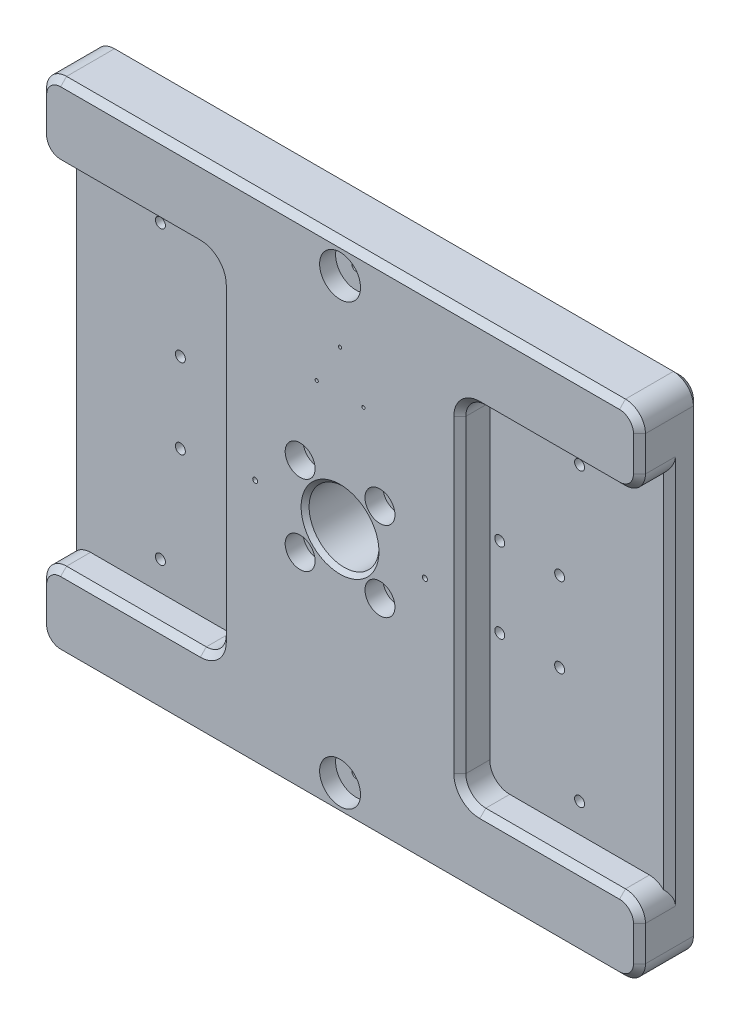
SolidWorks part; units mm, degrees
ref_plane "前视基准面" through (0, 0, 0) normal (0, 0, 1) x (1, 0, 0)
ref_plane "上视基准面" through (0, 0, 0) normal (0, 1, 0) x (1, 0, 0)
ref_plane "右视基准面" through (0, 0, 0) normal (1, 0, 0) x (0, 0, -1)
sketch "草图1" plane through (0, 0, 0) normal (0, 0, 1) x (1, 0, 0)
  line L1 (-150, 125) -> (150, 125)
  line L2 (-150, 125) -> (-150, -125)
  line L3 (-150, -125) -> (150, -125)
  line L4 (150, 125) -> (150, -125)
  line L5 (-150, 125) -> (150, -125) construction
  line L6 (-150, -125) -> (150, 125) construction
  point P0 (0, 0)
  dimension "D1" = 300
  dimension "D2" = 250
extrude "凸台-拉伸1" add sketch "草图1" along normal blind 30
sketch "草图2" plane through (0, 0, 30) normal (0, 0, 1) x (1, 0, 0)
  line L0 (-150, 125) -> (-150, -125) construction
  line L1 (-240, 87.5) -> (-60, 87.5)
  line L2 (-240, 87.5) -> (-240, -87.5)
  line L3 (-240, -87.5) -> (-60, -87.5)
  line L4 (-60, 87.5) -> (-60, -87.5)
  line L5 (-240, 87.5) -> (-60, -87.5) construction
  line L6 (-240, -87.5) -> (-60, 87.5) construction
  line L7 (150, -125) -> (150, 125) construction
  line L8 (240, -87.5) -> (60, -87.5)
  line L9 (240, -87.5) -> (240, 87.5)
  line L10 (240, 87.5) -> (60, 87.5)
  line L11 (60, -87.5) -> (60, 87.5)
  line L12 (240, -87.5) -> (60, 87.5) construction
  line L13 (240, 87.5) -> (60, -87.5) construction
  point P0 (-150, 0)
  point P7 (150, 0)
  dimension "D1" = 175
  dimension "D2" = 90
extrude "切除-拉伸1" cut sketch "草图2" against normal blind 15
fillet "圆角1" radius 10 12 edges at (150, -87.5, 22.5) (60, -87.5, 22.5) (150, 87.5, 22.5) (60, 87.5, 22.5) (-150, -87.5, 22.5) (-60, -87.5, 22.5) (-150, 87.5, 22.5) (-60, 87.5, 22.5) (-150, -125, 15) (150, -125, 15) (150, 125, 15) (-150, 125, 15)
hole_wizard "打孔尺寸(%根据)内六角圆柱头螺钉的类型1" positions "草图4" profile "草图5" counterbore size "M8" standard "GB" end condition through all
sketch "草图4" plane through (0, 0, 30) normal (0, 0, 1) x (1, 0, 0)
  point P0 (-20, 20)
  point P3 (20, 20)
  point P6 (20, -20)
  point P9 (-20, -20)
sketch "草图5" plane through (-20, 20, 30) normal (1, 0, 0) x (0, -1, 0)
  line L0 (0, 0) -> (0, 30)
  line L1 (0, 30) -> (4.5, 30)
  line L3 (4.5, 30) -> (4.5, 9)
  line L4 (4.5, 9) -> (7.5, 9)
  line L5 (7.5, 9) -> (7.5, 0)
  line L7 (7.5, 0) -> (0, 0)
  line L11 (0, -6.35) -> (0, 107.95) construction
  dimension "通孔孔直径" = 9
  dimension "通孔孔深度" = 30
  dimension "柱形沉头孔直径" = 15
  dimension "柱形沉头孔深度" = 9
chamfer "倒角1" distance 3 angle 45 34 edges at (0, -125, 0) (147.0711, -122.0711, 0) (-147.0711, -122.0711, 0) (150, 0, 0) (-150, 0, 0) (147.0711, 122.0711, 0) (-147.0711, 122.0711, 0) (0, 125, 0) (-105, 87.5, 30) (-147.0711, 90.4289, 30) (-62.9289, 84.5711, 30) (-150, 106.25, 30) (-60, 0, 30) (-147.0711, 122.0711, 30) (-62.9289, -84.5711, 30) (0, 125, 30) (-105, -87.5, 30) (147.0711, 122.0711, 30) (-147.0711, -90.4289, 30) (150, 106.25, 30) (-150, -106.25, 30) (147.0711, 90.4289, 30) (-147.0711, -122.0711, 30) (105, 87.5, 30) (0, -125, 30) (62.9289, 84.5711, 30) (147.0711, -122.0711, 30) (60, 0, 30) (150, -106.25, 30) (62.9289, -84.5711, 30) (147.0711, -90.4289, 30) (105, -87.5, 30) (-150, 0, 15) (150, 0, 15)
sketch "草图6" plane through (0, 0, 30) normal (0, 0, 1) x (1, 0, 0)
  circle A0 centre (0, 0) radius 17.5
  dimension "D1" = 35
extrude "切除-拉伸2" cut sketch "草图6" against normal through all
chamfer "倒角2" distance 2 angle 45 2 edges at (17.5, 0, 0) (17.5, 0, 30)
hole_wizard "M6 螺纹孔1" positions "草图7" profile "草图9" tap size "M6" standard "GB"
sketch "草图7" plane through (0, 0, 0) normal (0, 0, -1) x (-1, 0, 0)
  line L0 (23.3, -95) -> (16.7, -95) construction
  line L1 (23.3, -101) -> (23.3, -89) construction
  line L2 (16.7, -89) -> (16.7, -101) construction
  line L3 (-16.7, -95) -> (-23.3, -95) construction
  line L4 (-16.7, -101) -> (-16.7, -89) construction
  line L5 (-23.3, -89) -> (-23.3, -101) construction
  line L8 (-23.3, -65) -> (-16.7, -65) construction
  line L9 (-23.3, -59) -> (-23.3, -71) construction
  line L11 (-16.7, -71) -> (-16.7, -59) construction
  line L12 (23.3, -65) -> (16.7, -65) construction
  line L13 (23.3, -71) -> (23.3, -59) construction
  line L14 (16.7, -59) -> (16.7, -71) construction
  line L15 (65, -23.3) -> (65, -16.7) construction
  line L16 (59, -23.3) -> (71, -23.3) construction
  line L17 (71, -16.7) -> (59, -16.7) construction
  line L20 (95, -23.3) -> (95, -16.7) construction
  line L21 (89, -23.3) -> (101, -23.3) construction
  line L22 (101, -16.7) -> (89, -16.7) construction
  line L25 (95, 16.7) -> (95, 23.3) construction
  line L26 (89, 16.7) -> (101, 16.7) construction
  line L27 (101, 23.3) -> (89, 23.3) construction
  line L30 (65, 16.7) -> (65, 23.3) construction
  line L31 (59, 16.7) -> (71, 16.7) construction
  line L33 (71, 23.3) -> (59, 23.3) construction
  line L34 (-65, -23.3) -> (-65, -16.7) construction
  line L35 (-71, -23.3) -> (-59, -23.3) construction
  line L36 (-59, -16.7) -> (-71, -16.7) construction
  line L39 (-95, -23.3) -> (-95, -16.7) construction
  line L40 (-101, -23.3) -> (-89, -23.3) construction
  line L41 (-89, -16.7) -> (-101, -16.7) construction
  line L45 (-65, 16.7) -> (-65, 23.3) construction
  line L46 (-71, 16.7) -> (-59, 16.7) construction
  line L47 (-59, 23.3) -> (-71, 23.3) construction
  line L51 (-95, 16.7) -> (-95, 23.3) construction
  line L52 (-101, 16.7) -> (-89, 16.7) construction
  line L53 (-89, 23.3) -> (-101, 23.3) construction
  line L55 (23.3, 65) -> (16.7, 65) construction
  line L56 (23.3, 59) -> (23.3, 71) construction
  line L57 (16.7, 71) -> (16.7, 59) construction
  line L60 (-16.7, 65) -> (-23.3, 65) construction
  line L61 (-16.7, 59) -> (-16.7, 71) construction
  line L62 (-23.3, 71) -> (-23.3, 59) construction
  line L65 (23.3, 95) -> (16.7, 95) construction
  line L66 (23.3, 89) -> (23.3, 101) construction
  line L67 (16.7, 101) -> (16.7, 89) construction
  line L71 (-16.7, 95) -> (-23.3, 95) construction
  line L72 (-16.7, 89) -> (-16.7, 101) construction
  line L73 (-23.3, 101) -> (-23.3, 89) construction
  point P11 (20, -95)
  point P39 (-20, -95)
  point P41 (-20, -65)
  point P43 (20, -65)
  point P81 (65, -20)
  point P83 (95, -20)
  point P85 (95, 20)
  point P87 (65, 20)
  point P169 (-65, -20)
  point P171 (-95, -20)
  point P173 (-95, 20)
  point P175 (-65, 20)
  point P177 (20, 65)
  point P179 (20, 95)
  point P181 (-20, 65)
  point P183 (-20, 95)
sketch "草图9" plane through (20, 95, 0) normal (1, 0, 0) x (0, 1, 0)
  line L0 (0, 0) -> (0, 16.5022)
  line L1 (0, 16.5022) -> (2.5, 15)
  line L2 (2.5, 15) -> (2.5, 0)
  line L5 (2.5, 0) -> (0, 0)
  line L10 (0, 16.5022) -> (-2.5, 15) construction
  line L11 (0, -6.35) -> (0, 107.95) construction
  dimension "螺纹孔钻头直径" = 5
  dimension "螺纹孔钻头深度" = 15
  dimension "导头角度" = 118
cosmetic thread "孔螺蚊线1" parameters "D1"=12, "D2"=6
cosmetic thread "孔螺蚊线2" parameters "D1"=12, "D2"=6
cosmetic thread "孔螺蚊线3" parameters "D1"=12, "D2"=6
cosmetic thread "孔螺蚊线4" parameters "D1"=12, "D2"=6
cosmetic thread "孔螺蚊线5" parameters "D1"=12, "D2"=6
cosmetic thread "孔螺蚊线6" parameters "D1"=12, "D2"=6
cosmetic thread "孔螺蚊线7" parameters "D1"=12, "D2"=6
cosmetic thread "孔螺蚊线8" parameters "D1"=12, "D2"=6
cosmetic thread "孔螺蚊线9" parameters "D1"=12, "D2"=6
cosmetic thread "孔螺蚊线10" parameters "D1"=12, "D2"=6
cosmetic thread "孔螺蚊线11" parameters "D1"=12, "D2"=6
cosmetic thread "孔螺蚊线12" parameters "D1"=12, "D2"=6
cosmetic thread "孔螺蚊线13" parameters "D1"=12, "D2"=6
cosmetic thread "孔螺蚊线14" parameters "D1"=12, "D2"=6
cosmetic thread "孔螺蚊线15" parameters "D1"=12, "D2"=6
cosmetic thread "孔螺蚊线16" parameters "D1"=12, "D2"=6
hole_wizard "M6 螺纹孔2" positions "草图10" profile "草图11" tap size "M6" standard "GB" end condition through all
sketch "草图10" plane through (0, 0, 15) normal (0, 0, 1) x (1, 0, 0)
  point P0 (-105, 73)
  point P3 (-105, -73)
  point P6 (105, 73)
  point P9 (105, -73)
sketch "草图11" plane through (-105, 73, 15) normal (1, 0, 0) x (0, -1, 0)
  line L0 (0, 0) -> (0, 15)
  line L1 (0, 15) -> (2.5, 15)
  line L2 (2.5, 15) -> (2.5, 0)
  line L5 (2.5, 0) -> (0, 0)
  line L11 (0, -6.35) -> (0, 107.95) construction
  dimension "通孔螺纹孔钻头直径" = 5
  dimension "通孔螺纹孔钻头深度" = 15
cosmetic thread "孔螺蚊线17" parameters "D2"=6
cosmetic thread "孔螺蚊线18" parameters "D2"=6
cosmetic thread "孔螺蚊线19" parameters "D2"=6
cosmetic thread "孔螺蚊线20" parameters "D2"=6
hole_wizard "M5 螺纹孔1" positions "草图12" profile "草图13" tap size "M5" standard "GB"
sketch "草图12" plane through (0, -125, 0) normal (0, -1, 0) x (-1, 0, 0)
  point P0 (65, -15)
  point P3 (-65, -15)
sketch "草图13" plane through (-65, -125, 15) normal (1, 0, 0) x (0, 0, -1)
  line L0 (0, 0) -> (0, 13.6618)
  line L1 (0, 13.6618) -> (2.1, 12.4)
  line L2 (2.1, 12.4) -> (2.1, 0)
  line L5 (2.1, 0) -> (0, 0)
  line L10 (0, 13.6618) -> (-2.1, 12.4) construction
  line L11 (0, -6.35) -> (0, 107.95) construction
  dimension "螺纹孔钻头直径" = 4.2
  dimension "螺纹孔钻头深度" = 12.4
  dimension "导头角度" = 118
cosmetic thread "孔螺蚊线21" parameters "D1"=10, "D2"=5
cosmetic thread "孔螺蚊线22" parameters "D1"=10, "D2"=5
hole_wizard "M2 螺纹孔1" positions "草图14" profile "草图15" tap size "M2" standard "GB"
sketch "草图14" plane through (0, 0, 30) normal (0, 0, 1) x (1, 0, 0)
  point P0 (11.6913, 58.75)
  point P3 (0, 79)
  point P5 (-11.6913, 58.75)
sketch "草图15" plane through (11.6913, 58.75, 30) normal (1, 0, 0) x (0, -1, 0)
  line L0 (0, 0) -> (0, 9.6807)
  line L1 (0, 9.6807) -> (0.8, 9.2)
  line L2 (0.8, 9.2) -> (0.8, 0)
  line L5 (0.8, 0) -> (0, 0)
  line L10 (0, 9.6807) -> (-0.8, 9.2) construction
  line L11 (0, -6.35) -> (0, 107.95) construction
  dimension "螺纹孔钻头直径" = 1.6
  dimension "螺纹孔钻头深度" = 9.2
  dimension "导头角度" = 118
cosmetic thread "孔螺蚊线23" parameters "D1"=8, "D2"=2
cosmetic thread "孔螺蚊线24" parameters "D1"=8, "D2"=2
cosmetic thread "孔螺蚊线25" parameters "D1"=8, "D2"=2
hole_wizard "M3 螺纹孔1" positions "草图19" profile "草图20" tap size "M3" standard "GB"
sketch "草图19" plane through (0, 0, 30) normal (0, 0, 1) x (1, 0, 0)
  line L0 (-42.5, 0) -> (42.5, 0) construction
  point P0 (-42.5, 0)
  point P1 (42.5, 0)
  point P4 (0, 0)
  dimension "D1" = 85
sketch "草图20" plane through (-42.5, 0, 30) normal (1, 0, 0) x (0, -1, 0)
  line L0 (0, 0) -> (0, 10.2511)
  line L1 (0, 10.2511) -> (1.25, 9.5)
  line L2 (1.25, 9.5) -> (1.25, 0)
  line L5 (1.25, 0) -> (0, 0)
  line L10 (0, 10.2511) -> (-1.25, 9.5) construction
  line L11 (0, -6.35) -> (0, 107.95) construction
  dimension "螺纹孔钻头直径" = 2.5
  dimension "螺纹孔钻头深度" = 9.5
  dimension "导头角度" = 118
cosmetic thread "孔螺蚊线26" parameters "D1"=8, "D2"=3
cosmetic thread "孔螺蚊线27" parameters "D1"=8, "D2"=3
sketch "草图21" plane through (0, 0, 30) normal (0, 0, 1) x (1, 0, 0)
  line L0 (0, 110) -> (0, -110) construction
  circle A0 centre (0, 110) radius 10.25
  circle A1 centre (0, -110) radius 10.25
  point P5 (0, 0)
  dimension "D1" = 20.5
  dimension "D2" = 220
extrude "切除-拉伸3" cut sketch "草图21" against normal blind 8
hole_wizard "M5 螺纹孔2" positions "草图22" profile "草图23" tap size "M5" standard "GB"
sketch "草图22" plane through (0, 0, 22) normal (0, 0, 1) x (1, 0, 0)
  point P0 (0, -110)
  point P3 (0, 110)
sketch "草图23" plane through (0, -110, 22) normal (1, 0, 0) x (0, -1, 0)
  line L0 (0, 0) -> (0, 13.6618)
  line L1 (0, 13.6618) -> (2.1, 12.4)
  line L2 (2.1, 12.4) -> (2.1, 0)
  line L5 (2.1, 0) -> (0, 0)
  line L10 (0, 13.6618) -> (-2.1, 12.4) construction
  line L11 (0, -6.35) -> (0, 107.95) construction
  dimension "螺纹孔钻头直径" = 4.2
  dimension "螺纹孔钻头深度" = 12.4
  dimension "导头角度" = 118
cosmetic thread "孔螺蚊线28" parameters "D1"=10, "D2"=5
cosmetic thread "孔螺蚊线29" parameters "D1"=10, "D2"=5
